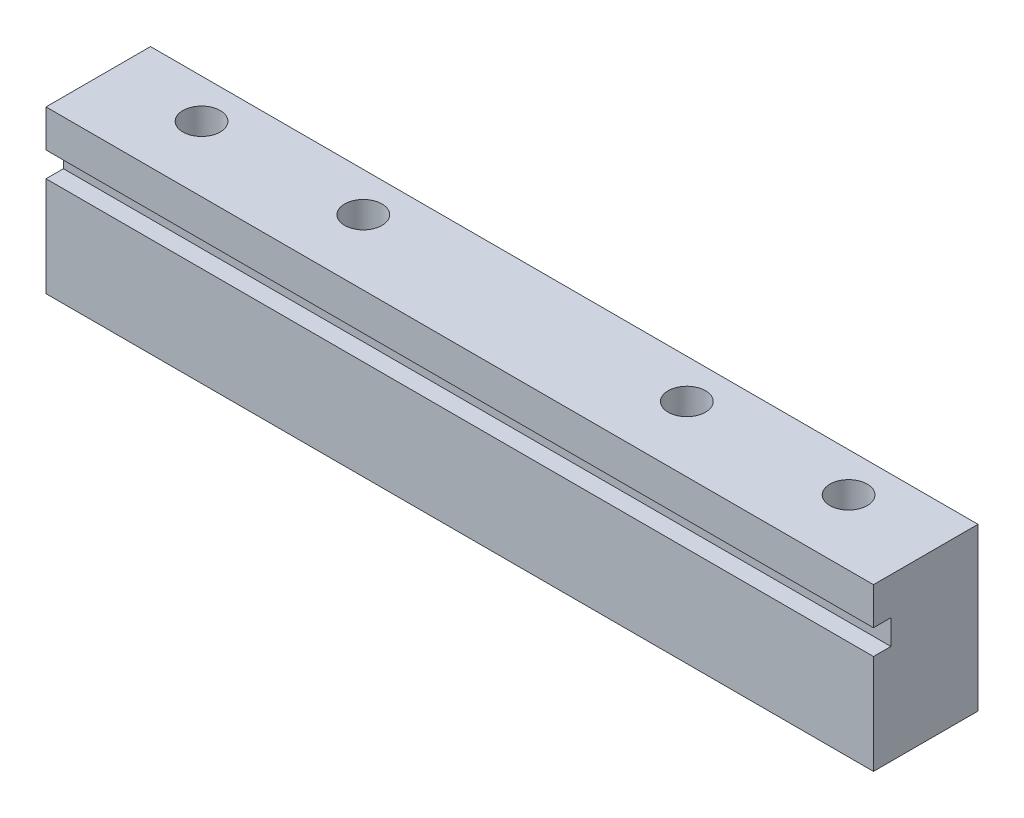
SolidWorks part; units mm, degrees
ref_plane "前视基准面" through (0, 0, 0) normal (0, 0, 1) x (1, 0, 0)
ref_plane "上视基准面" through (0, 0, 0) normal (0, 1, 0) x (1, 0, 0)
ref_plane "右视基准面" through (0, 0, 0) normal (1, 0, 0) x (0, 0, -1)
sketch "草图1" plane through (0, 0, 0) normal (0, 1, 0) x (1, 0, 0)
  line L1 (-33.25, 4.2) -> (33.25, 4.2)
  line L2 (-33.25, 4.2) -> (-33.25, -4.2)
  line L3 (-33.25, -4.2) -> (33.25, -4.2)
  line L4 (33.25, 4.2) -> (33.25, -4.2)
  line L5 (-33.25, 4.2) -> (33.25, -4.2) construction
  line L6 (-33.25, -4.2) -> (33.25, 4.2) construction
  point P0 (0, 0)
  dimension "D1" = 8.4
  dimension "D2" = 66.5
extrude "凸台-拉伸1" add sketch "草图1" along normal blind 13
sketch "草图2" plane through (33.25, 0, 0) normal (1, 0, 0) x (0, 0, -1)
  line L0 (-4.2, 13) -> (-4.2, 0) construction
  line L1 (-4.2, 10) -> (-2.8, 10)
  line L2 (-4.2, 10) -> (-4.2, 8)
  line L3 (-4.2, 8) -> (-2.8, 8)
  line L4 (-2.8, 10) -> (-2.8, 8)
  line L5 (-4.2, 13) -> (4.2, 13) construction
  line L8 (4.2, 13) -> (4.2, 0) construction
  dimension "D1" = 3
  dimension "D2" = 5
  dimension "D3" = 7
extrude "切除-拉伸1" cut sketch "草图2" against normal blind 104
ref_plane "基准面1" through (0, 0, 0) normal (1, 0, 0) x (0, 0, -1)
sketch "草图4" plane through (0, 0, 0) normal (0, -1, 0) x (1, 0, 0)
  circle A4 centre (-26, -1.05) radius 1.5
  circle A5 centre (-13, -1.05) radius 1.5
  circle A6 centre (26, -1.05) radius 1.5
  circle A7 centre (13, -1.05) radius 1.5
extrude "切除-拉伸3" cut sketch "草图4" against normal through all
